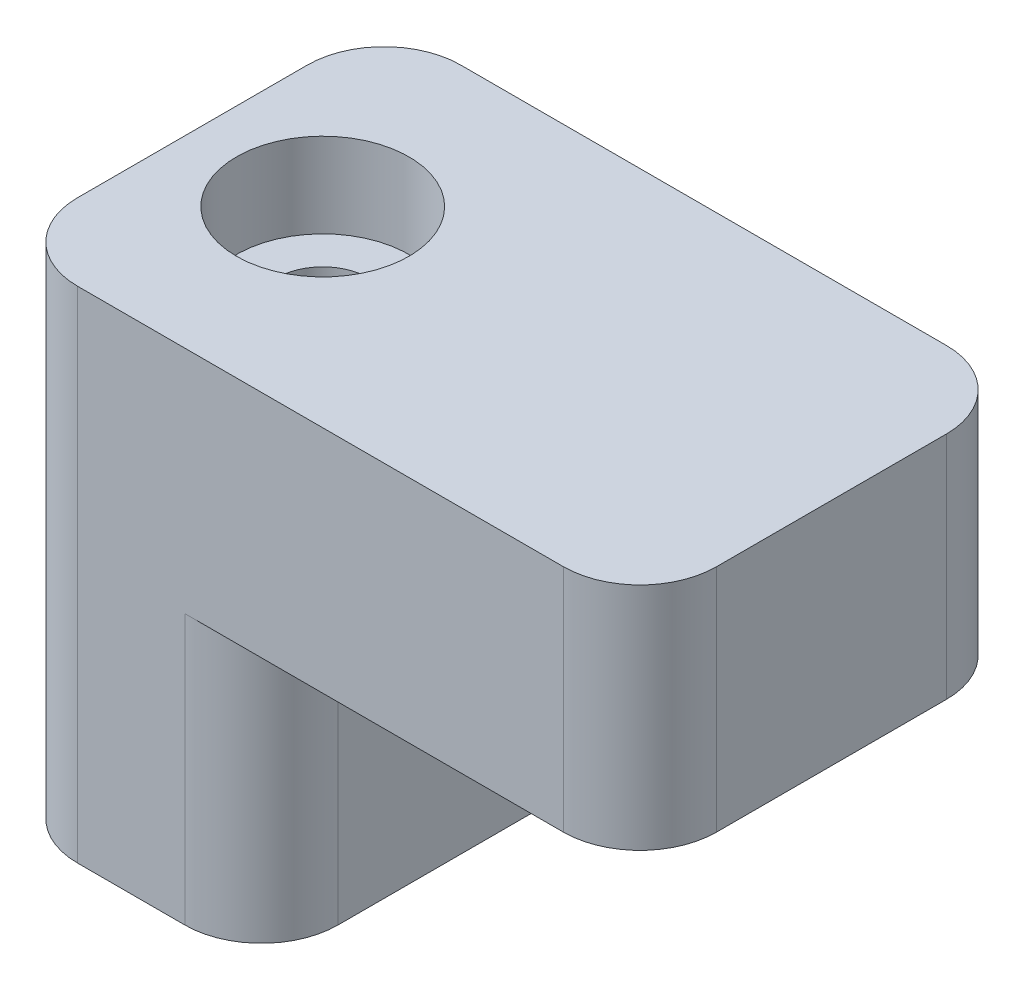
SolidWorks part; units mm, degrees
ref_plane "Front Plane" through (0, 0, 0) normal (0, 0, 1) x (1, 0, 0)
ref_plane "Top Plane" through (0, 0, 0) normal (0, 1, 0) x (1, 0, 0)
ref_plane "Right Plane" through (0, 0, 0) normal (1, 0, 0) x (0, 0, -1)
sketch "Sketch1" plane through (0, 0, 0) normal (0, 0, 1) x (1, 0, 0)
  line L0 (0, 0) -> (0, 20.701)
  line L1 (0, 20.701) -> (26.4795, 20.701)
  line L2 (26.4795, 20.701) -> (26.4795, 11.176)
  line L3 (26.4795, 11.176) -> (10.795, 11.176)
  line L4 (10.795, 11.176) -> (10.795, 0)
  line L5 (10.795, 0) -> (0, 0)
  point P3 (5.3975, 0)
  point P8 (22.6695, 11.176)
  dimension "D1" = 9.525
  dimension "D2" = 10.795
  dimension "D3" = 11.176
  dimension "D4" = 3.81
  dimension "D5" = 17.272
extrude "Boss-Extrude1" add sketch "Sketch1" against normal blind 15.875
hole_wizard "CBORE for #6 Socket Head Cap Screw1" positions "Sketch3" profile "Sketch2" counterbore size "#6" standard "ANSI Inch" end condition through all
sketch "Sketch3" plane through (0, 20.701, 0) normal (0, 1, 0) x (1, 0, 0)
  line L0 (10.795, 15.875) -> (10.795, 0) construction
  line L1 (10.795, 15.875) -> (10.795, 0) construction
  line L2 (0, 15.875) -> (10.795, 0) construction
  line L4 (0, 0) -> (10.795, 15.875) construction
  point P0 (5.3975, 7.9375)
sketch "Sketch2" plane through (5.3975, 20.701, -7.9375) normal (1, 0, 0) x (0, 0, 1)
  line L0 (0, 0) -> (0, 20.701)
  line L1 (0, 20.701) -> (1.8986, 20.701)
  line L3 (1.8986, 20.701) -> (1.8986, 3.5052)
  line L4 (1.8986, 3.5052) -> (3.5725, 3.5052)
  line L5 (3.5725, 3.5052) -> (3.5725, 0)
  line L7 (3.5725, 0) -> (0, 0)
  line L11 (0, -6.35) -> (0, 107.95) construction
  dimension "Thru Hole Dia." = 3.7973
  dimension "Thru Hole Depth" = 20.701
  dimension "C'Bore Dia." = 7.145
  dimension "C'Bore Depth" = 3.5052
sketch "Sketch5" plane through (0, 11.176, 0) normal (0, -1, 0) x (1, 0, 0)
  line L0 (10.795, -7.9375) -> (26.4795, -7.9375) construction
  line L1 (10.795, -15.875) -> (10.795, 0) construction
  line L2 (26.4795, -15.875) -> (26.4795, 0) construction
  line L3 (20.3835, -2.6035) -> (24.9555, -2.6035) construction
  line L4 (20.3835, -2.2066) -> (24.9555, -2.2066)
  line L5 (20.3835, -3.0004) -> (24.9555, -3.0004)
  line L6 (20.3835, -13.2715) -> (24.9555, -13.2715) construction
  line L7 (20.3835, -12.8746) -> (24.9555, -12.8746)
  line L8 (20.3835, -13.6684) -> (24.9555, -13.6684)
  arc A0 (20.3835, -2.2066) -> (20.3835, -3.0004) centre (20.3835, -2.6035) ccw
  arc A1 (24.9555, -3.0004) -> (24.9555, -2.2066) centre (24.9555, -2.6035) ccw
  arc A2 (20.3835, -12.8746) -> (20.3835, -13.6684) centre (20.3835, -13.2715) ccw
  arc A3 (24.9555, -13.6684) -> (24.9555, -12.8746) centre (24.9555, -13.2715) ccw
  circle A4 centre (5.3975, -7.9375) radius 1.8986 construction
  point P8 (22.6695, -2.6035)
  point P13 (22.6695, -13.2715)
  dimension "D5" = 17.272
  dimension "D1" = 4.572
  dimension "D2" = 10.668
  dimension "D3" = 5.334
  dimension "D4" = 0.7937
extrude "Cut-Extrude2" cut sketch "Sketch5" against normal blind 2.54
fillet "Fillet1" radius 3.175 6 edges at (10.795, 5.588, -15.875) (10.795, 5.588, 0) (0, 10.3505, -15.875) (0, 10.3505, 0) (26.4795, 15.9385, -15.875) (26.4795, 15.9385, 0)
